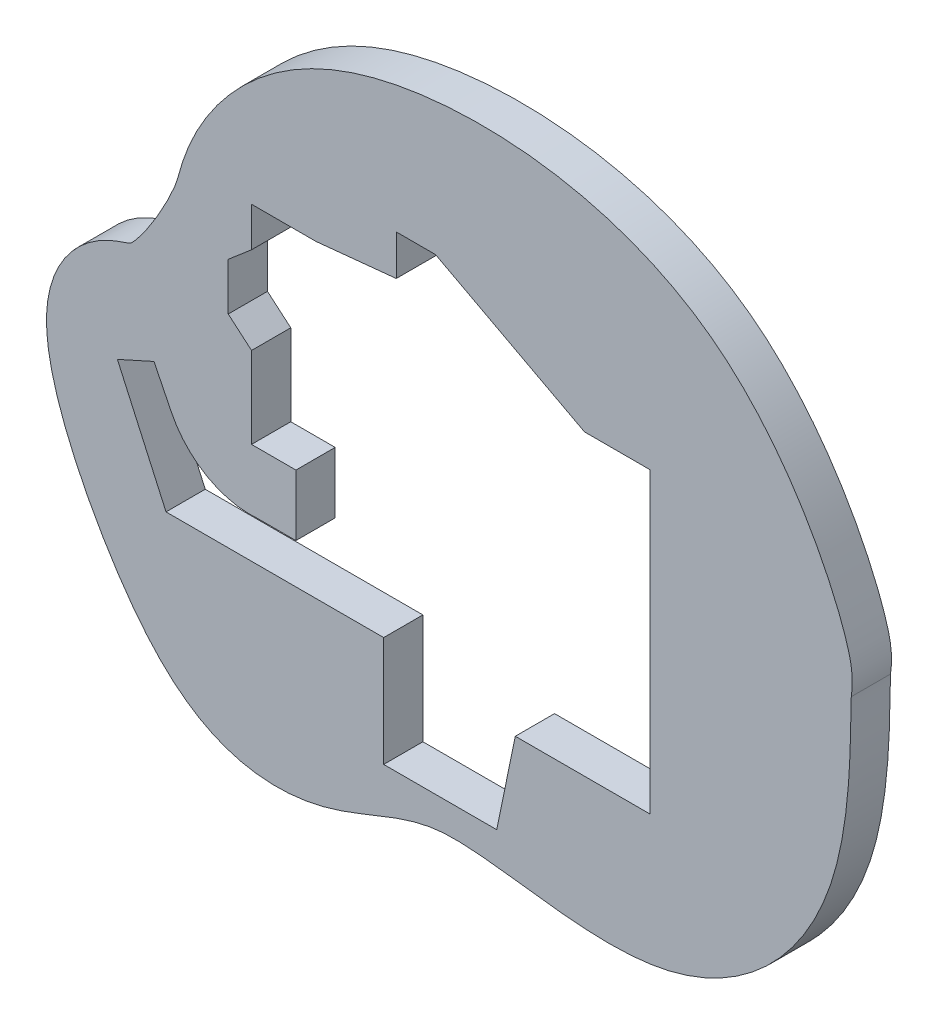
SolidWorks part; units mm, degrees
ref_plane "Front Plane" through (0, 0, 0) normal (0, 0, 1) x (1, 0, 0)
ref_plane "Top Plane" through (0, 0, 0) normal (0, 1, 0) x (1, 0, 0)
ref_plane "Right Plane" through (0, 0, 0) normal (1, 0, 0) x (0, 0, -1)
ref_plane "Plane1" through (0, 0, 3) normal (0, 0, 1) x (1, 0, 0)
sketch "Sketch1" plane through (0, 0, 3) normal (0, 0, 1) x (1, 0, 0)
  line L0 (-27.9027, 87.5573) -> (-38.1933, 87.5573)
  line L1 (-38.1933, 87.5573) -> (-39.6137, 80.6595)
  line L2 (-39.6137, 80.6595) -> (-48.2575, 80.6595)
  line L3 (-48.2575, 80.6595) -> (-48.2575, 89.0603)
  line L4 (-48.2575, 89.0603) -> (-64.8991, 89.0603)
  line L5 (-64.8991, 89.0603) -> (-68.6175, 97.3009)
  line L6 (-68.6175, 97.3009) -> (-65.8208, 98.5628)
  line L7 (-65.8208, 98.5628) -> (-64.4869, 95.8651)
  line L8 (-57.8224, 92.1285) -> (-54.9668, 92.1285)
  line L9 (-54.9668, 92.1285) -> (-54.9668, 96.7987)
  line L10 (-54.9668, 96.7987) -> (-58.3615, 96.7987)
  line L11 (-58.3615, 96.7987) -> (-58.3615, 103.0209)
  line L12 (-58.3615, 103.0209) -> (-60.1432, 104.5412)
  line L13 (-60.1432, 104.5412) -> (-60.1432, 108.1657)
  line L14 (-60.1432, 108.1657) -> (-58.3615, 109.6857)
  line L15 (-58.3615, 109.6857) -> (-58.3615, 112.7028)
  line L16 (-58.3615, 112.7028) -> (-53.4332, 112.7028)
  line L17 (-53.4332, 112.7028) -> (-47.2937, 113.3186)
  line L18 (-47.2937, 113.3186) -> (-47.2937, 116.4033)
  line L19 (-47.2937, 116.4033) -> (-44.2937, 116.4033)
  line L20 (-44.2937, 116.4033) -> (-32.9027, 110.3573)
  line L21 (-32.9027, 110.3573) -> (-27.9027, 110.3573)
  line L22 (-27.9027, 110.3573) -> (-27.9027, 87.5573)
  arc A0 (-64.4869, 95.8651) -> (-57.8224, 92.1285) centre (-58.4273, 98.8613) ccw
  spline S0 degree 3 poles (-12.5037, 103.0209) (-12.5043, 103.0168) (-12.505, 103.0109) (-12.5055, 103.0065) (-12.5057, 103.0045) (-12.5059, 103.0026) (-12.506, 103.0007) (-12.5069, 102.9892) (-12.5087, 102.9634) (-12.5108, 102.927) (-12.5138, 102.8657) (-12.5178, 102.7676) (-12.5223, 102.6212) (-12.5263, 102.4498) (-12.5313, 102.1916) (-12.5368, 101.8188) (-12.5439, 101.3038) (-12.5535, 100.7298) (-12.5674, 100.1038) (-12.5879, 99.4318) (-12.6268, 98.4813) (-12.7024, 97.2033) (-12.8294, 95.834) (-12.972, 94.699) (-13.1025, 93.8316) (-13.2593, 92.9511) (-13.415, 92.2093) (-13.5565, 91.6123) (-13.6715, 91.1632) (-13.7754, 90.7882) (-13.8635, 90.4878) (-13.9553, 90.1871) (-14.0759, 89.8135) (-14.2812, 89.2222) (-14.561, 88.4949) (-14.9334, 87.6425) (-15.4787, 86.5347) (-16.2511, 85.2076) (-17.3218, 83.7194) (-18.5342, 82.349) (-19.885, 81.112) (-21.1216, 80.2062) (-22.1732, 79.5655) (-22.9917, 79.1292) (-23.8383, 78.7392) (-24.7112, 78.3976) (-25.4589, 78.1548) (-26.0682, 77.9867) (-26.4531, 77.8926) (-26.7639, 77.8239) (-27.0743, 77.7601) (-27.4611, 77.6893) (-27.9231, 77.6176) (-28.5357, 77.5384) (-29.2948, 77.4683) (-30.1941, 77.4237) (-31.0812, 77.4127) (-32.2473, 77.4358) (-33.673, 77.5228) (-35.3295, 77.6863) (-36.9254, 77.8789) (-38.4507, 78.074) (-39.8914, 78.247) (-41.0059, 78.3545) (-41.8342, 78.4095) (-42.4203, 78.4337) (-42.8765, 78.4385) (-43.2202, 78.433) (-43.4257, 78.4257) (-43.5844, 78.4175) (-43.7004, 78.4102) (-43.8139, 78.4018) (-43.9651, 78.3888) (-44.1527, 78.3695) (-44.4512, 78.3321) (-44.8215, 78.2735) (-45.2639, 78.1852) (-45.7064, 78.0799) (-46.2988, 77.9177) (-47.0475, 77.6767) (-47.9692, 77.3355) (-48.7648, 77.0178) (-49.4239, 76.7512) (-49.9317, 76.5475) (-50.4552, 76.3425) (-50.9068, 76.1731) (-51.2788, 76.0402) (-51.5636, 75.9423) (-51.8545, 75.8468) (-52.1526, 75.7542) (-52.4513, 75.6669) (-52.8518, 75.5575) (-53.356, 75.4343) (-53.9673, 75.3097) (-54.791, 75.1766) (-55.8367, 75.0768) (-57.1134, 75.0788) (-58.401, 75.2173) (-59.682, 75.5035) (-60.9347, 75.9418) (-62.1335, 76.526) (-63.2605, 77.2392) (-64.3126, 78.0629) (-65.2979, 78.9836) (-66.2307, 79.995) (-67.1275, 81.0967) (-68.0043, 82.293) (-68.8746, 83.5909) (-69.7283, 84.974) (-70.5531, 86.4255) (-71.3342, 87.9274) (-72.056, 89.4633) (-72.5945, 90.76) (-72.9785, 91.8035) (-73.2407, 92.5893) (-73.4742, 93.3789) (-73.6757, 94.174) (-73.8412, 94.9781) (-73.9442, 95.6598) (-74.0015, 96.2158) (-74.0304, 96.6394) (-74.0414, 96.9988) (-74.0412, 97.2907) (-74.0379, 97.4386) (-74.0353, 97.5127) knots 0.5 0.5 0.5 0.5 0.500977 0.501953 0.50293 0.503418 0.503906 0.504883 0.505859 0.506836 0.507812 0.509766 0.511719 0.513672 0.515625 0.519531 0.523438 0.527344 0.53125 0.535156 0.539062 0.546875 0.554688 0.558594 0.5625 0.566406 0.570312 0.572266 0.574219 0.576172 0.577148 0.578125 0.580078 0.582031 0.585938 0.589844 0.59375 0.601562 0.609375 0.617188 0.625 0.632812 0.636719 0.640625 0.644531 0.648438 0.652344 0.654297 0.65625 0.657227 0.658203 0.660156 0.662109 0.664062 0.667969 0.671875 0.675781 0.679688 0.6875 0.695312 0.703125 0.710938 0.71875 0.726562 0.730469 0.734375 0.738281 0.740234 0.742188 0.743164 0.744141 0.745117 0.746094 0.748047 0.75 0.753906 0.757812 0.761719 0.765625 0.773438 0.78125 0.789062 0.792969 0.796875 0.800781 0.804688 0.806641 0.808594 0.810547 0.8125 0.814453 0.816406 0.820312 0.824219 0.828125 0.835938 0.84375 0.851562 0.859375 0.867188 0.875 0.882812 0.890625 0.898438 0.90625 0.914062 0.921875 0.929688 0.9375 0.945312 0.953125 0.960938 0.96875 0.972656 0.976562 0.980469 0.984375 0.988281 0.992188 0.994141 0.996094 0.998047 0.999023 1 1 1 1
  spline S1 degree 3 poles (-74.0353, 97.5127) (-74.0328, 97.5868) (-74.0261, 97.7353) (-74.0058, 98.0302) (-73.9676, 98.3963) (-73.9011, 98.8299) (-73.7852, 99.3992) (-73.5893, 100.0909) (-73.2767, 100.8785) (-72.8939, 101.6135) (-72.4506, 102.2879) (-71.9578, 102.8961) (-71.5154, 103.3459) (-71.1475, 103.6717) (-70.8656, 103.8992) (-70.5789, 104.1103) (-70.3366, 104.2727) (-70.1411, 104.3949) (-69.9937, 104.4827) (-69.8458, 104.5666) (-69.6967, 104.6471) (-69.5506, 104.722) (-69.3607, 104.8148) (-69.1338, 104.918) (-68.8816, 105.0233) (-68.5752, 105.1421) (-68.2528, 105.256) (-67.9679, 105.353) (-67.7796, 105.4202) (-67.6745, 105.4626) (-67.6386, 105.4798) (-67.6276, 105.4856) (-67.6245, 105.4874) (-67.623, 105.4884) (-67.6204, 105.4901) (-67.616, 105.4934) (-67.612, 105.4964) (-67.6078, 105.4997) (-67.6033, 105.5034) (-67.5939, 105.5112) (-67.5766, 105.5263) (-67.5465, 105.5535) (-67.4772, 105.6192) (-67.3401, 105.7612) (-67.135, 105.9967) (-66.9033, 106.2861) (-66.6547, 106.6193) (-66.3966, 106.9871) (-66.0477, 107.5122) (-65.6148, 108.2136) (-65.2128, 108.9247) (-64.9236, 109.4693) (-64.7263, 109.8577) (-64.5812, 110.1574) (-64.4785, 110.3777) (-64.4089, 110.5317) (-64.3472, 110.6726) (-64.2756, 110.842) (-64.2013, 111.029) (-64.1303, 111.223) (-64.0703, 111.4015) (-64.0145, 111.5809) (-63.9567, 111.7786) (-63.8915, 112.0094) (-63.8142, 112.2826) (-63.7361, 112.5472) (-63.6727, 112.7507) (-63.634, 112.8711) (-63.5743, 113.0534) (-63.4776, 113.3345) (-63.3327, 113.7242) (-63.1708, 114.1278) (-62.9311, 114.6827) (-62.5842, 115.405) (-62.1684, 116.1584) (-61.7913, 116.7755) (-61.4854, 117.2444) (-61.1559, 117.7185) (-60.6809, 118.3597) (-60.019, 119.1727) (-59.1084, 120.1518) (-58.0756, 121.1184) (-56.9158, 122.0561) (-55.6255, 122.948) (-54.4397, 123.6392) (-53.4243, 124.1529) (-52.6295, 124.5167) (-51.8013, 124.8572) (-51.0836, 125.12) (-50.4927, 125.3169) (-49.8944, 125.5037) (-49.132, 125.7189) (-48.1951, 125.9483) (-46.9182, 126.2162) (-45.2733, 126.4802) (-43.2325, 126.6818) (-40.4393, 126.7915) (-37.5641, 126.6525) (-34.6639, 126.2347) (-32.4914, 125.7721) (-30.3375, 125.1494) (-28.5724, 124.4867) (-27.188, 123.8634) (-26.1662, 123.3475) (-25.1638, 122.7814) (-24.3474, 122.2663) (-23.7074, 121.8274) (-23.3133, 121.5418) (-23.0015, 121.3062) (-22.694, 121.0673) (-22.3177, 120.7631) (-21.8789, 120.3897) (-21.3104, 119.8817) (-20.3583, 118.9693) (-19.1152, 117.6129) (-17.7966, 115.9423) (-16.6399, 114.2668) (-15.6361, 112.6226) (-14.7784, 111.044) (-14.1808, 109.8108) (-13.7704, 108.8881) (-13.4958, 108.231) (-13.2535, 107.6111) (-13.0426, 107.029) (-12.8614, 106.4825) (-12.7336, 106.0506) (-12.6437, 105.7079) (-12.5922, 105.4897) (-12.5537, 105.3078) (-12.5171, 105.1181) (-12.4761, 104.8671) (-12.4387, 104.5404) (-12.4189, 104.1961) (-12.4199, 103.8557) (-12.4383, 103.5509) (-12.4639, 103.3104) (-12.4859, 103.1472) (-12.4991, 103.0555) (-12.5026, 103.0292) (-12.5037, 103.0209) knots 0 0 0 0 0.000977 0.001953 0.003906 0.005859 0.007812 0.011719 0.015625 0.019531 0.023438 0.027344 0.03125 0.033203 0.035156 0.037109 0.039062 0.040039 0.041016 0.041992 0.042969 0.043945 0.044922 0.046875 0.048828 0.050781 0.054688 0.058594 0.0625 0.066406 0.070312 0.072266 0.074219 0.076172 0.078125 0.079102 0.080078 0.080566 0.081055 0.082031 0.083008 0.083984 0.085938 0.089844 0.09375 0.097656 0.101562 0.105469 0.109375 0.117188 0.125 0.128906 0.132812 0.136719 0.138672 0.140625 0.142578 0.144531 0.148438 0.152344 0.15625 0.160156 0.164062 0.167969 0.171875 0.175781 0.177734 0.178711 0.179688 0.183594 0.1875 0.191406 0.195312 0.203125 0.210938 0.214844 0.21875 0.222656 0.226562 0.234375 0.242188 0.25 0.257812 0.265625 0.273438 0.277344 0.28125 0.285156 0.289062 0.291016 0.292969 0.296875 0.300781 0.304688 0.3125 0.320312 0.328125 0.34375 0.351562 0.359375 0.367188 0.375 0.378906 0.382812 0.386719 0.390625 0.392578 0.394531 0.395508 0.396484 0.398438 0.400391 0.402344 0.40625 0.414062 0.421875 0.429688 0.4375 0.445312 0.453125 0.457031 0.460938 0.464844 0.46875 0.472656 0.476562 0.478516 0.480469 0.481445 0.482422 0.484375 0.486328 0.488281 0.490234 0.492188 0.494141 0.496094 0.498047 0.5 0.5 0.5 0.5
  dimension "D5" = 6.7599
  dimension "D1" = 22.8
  dimension "D2" = 5
  dimension "D3" = 11.391
  dimension "D4" = 3
  dimension "D14" = 2.342
  dimension "D28" = 130.47
  dimension "D30" = 3.017
extrude "Boss-Extrude1" add sketch "Sketch1" along normal blind 3
